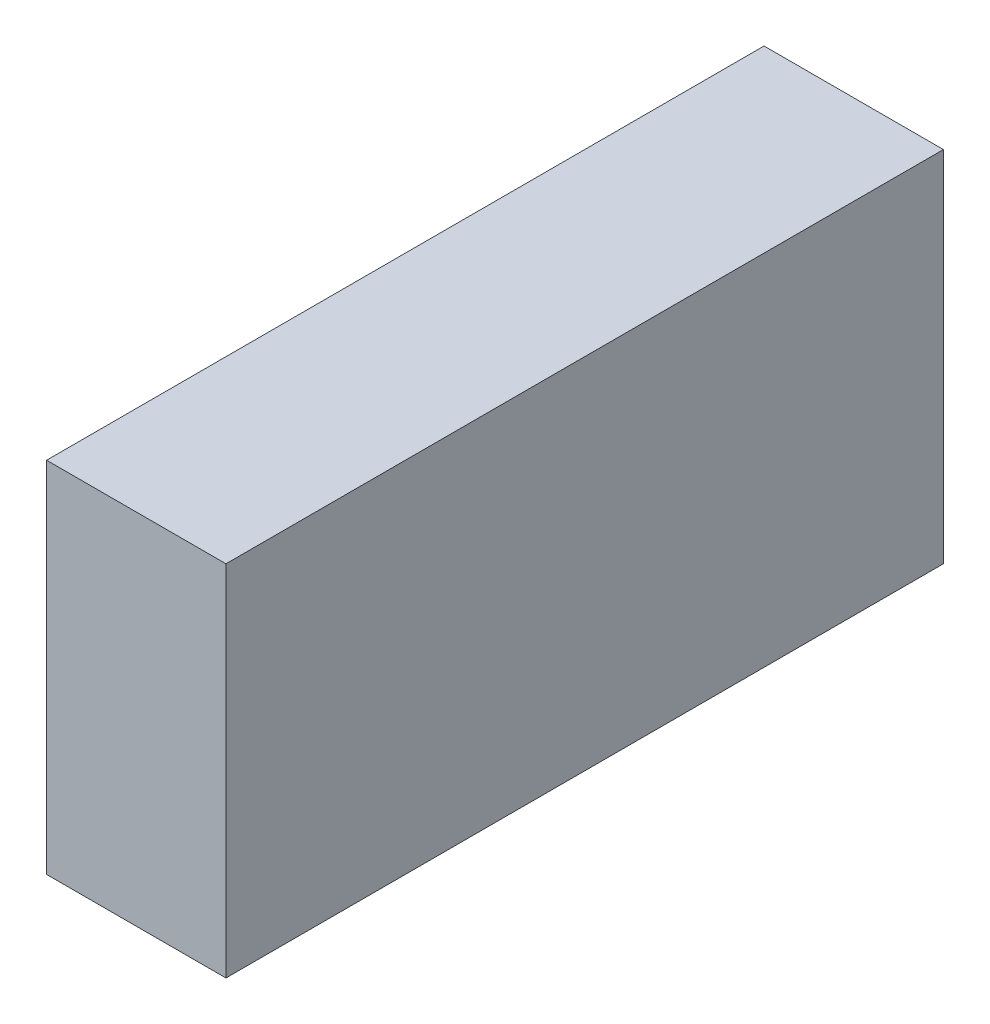
SolidWorks part; units mm, degrees
ref_plane "正面" through (0, 0, 0) normal (0, 0, 1) x (1, 0, 0)
ref_plane "平面" through (0, 0, 0) normal (0, 1, 0) x (1, 0, 0)
ref_plane "右側面" through (0, 0, 0) normal (1, 0, 0) x (0, 0, -1)
sketch "ｽｹｯﾁ1" plane through (0, 0, 0) normal (0, 0, 1) x (1, 0, 0)
  line L1 (0, 0) -> (10, 0)
  line L2 (0, 0) -> (0, 20)
  line L3 (0, 20) -> (10, 20)
  line L4 (10, 0) -> (10, 20)
  dimension "D1" = 20
  dimension "D2" = 10
extrude "押し出し1" add sketch "ｽｹｯﾁ1" along normal blind 40
